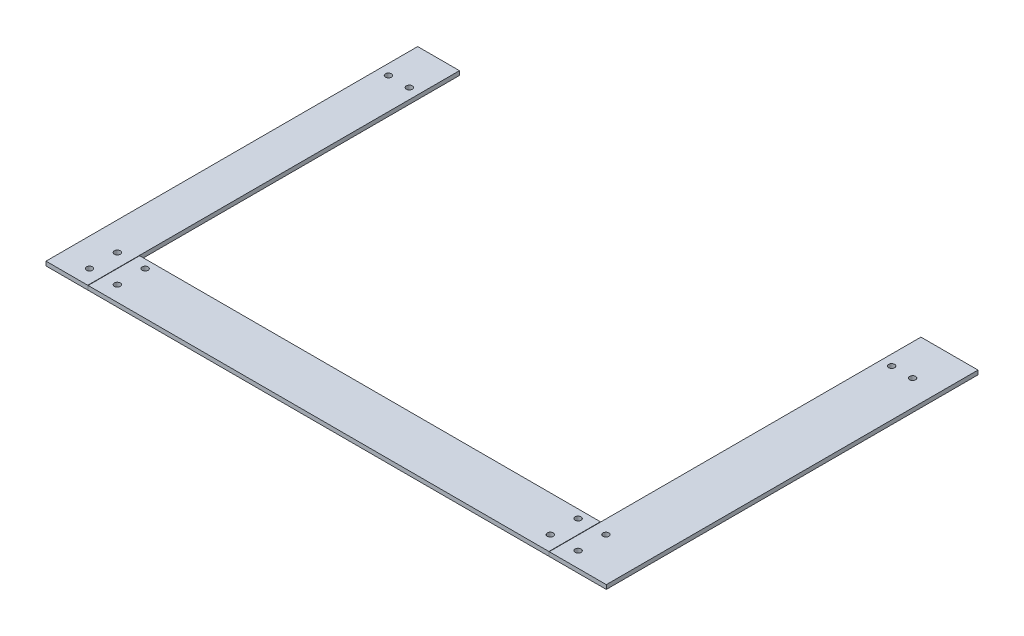
SolidWorks part; units mm, degrees
ref_plane "Front Plane" through (0, 0, 0) normal (0, 0, 1) x (1, 0, 0)
ref_plane "Top Plane" through (0, 0, 0) normal (0, 1, 0) x (1, 0, 0)
ref_plane "Right Plane" through (0, 0, 0) normal (1, 0, 0) x (0, 0, -1)
sketch "Sketch1" plane through (0, 0, 0) normal (0, 1, 0) x (1, 0, 0)
  line L1 (165.75, -135.5) -> (206.75, -135.5)
  line L2 (165.75, -135.5) -> (165.75, 131.5)
  line L3 (165.75, 131.5) -> (206.75, 131.5)
  line L4 (206.75, -135.5) -> (206.75, 131.5)
  line L5 (165.75, -135.5) -> (206.75, 131.5) construction
  line L6 (165.75, 131.5) -> (206.75, -135.5) construction
  point P0 (186.25, -2)
  dimension "D1" = 267
  dimension "D2" = 41
  dimension "D3" = 165.75
  dimension "D4" = 2
extrude "Boss-Extrude1" add sketch "Sketch1" along normal blind 3
sketch "Sketch2" plane through (0, 0, 0) normal (0, 1, 0) x (1, 0, 0)
  line L1 (-195.75, -135.5) -> (-165.75, -135.5)
  line L2 (-195.75, -135.5) -> (-195.75, 131.5)
  line L3 (-195.75, 131.5) -> (-165.75, 131.5)
  line L4 (-165.75, -135.5) -> (-165.75, 131.5)
  line L5 (-195.75, -135.5) -> (-165.75, 131.5) construction
  line L6 (-195.75, 131.5) -> (-165.75, -135.5) construction
  point P0 (-180.75, -2)
  dimension "D1" = 30
  dimension "D2" = 267
  dimension "D3" = 2
  dimension "D4" = 165.75
extrude "Boss-Extrude2" add sketch "Sketch2" along normal blind 3 separate body
sketch "Sketch3" plane through (0, 0, 0) normal (0, 1, 0) x (1, 0, 0)
  line L0 (-195.75, -135.5) -> (-165.75, -135.5) construction
  line L1 (-165.5, -135.5) -> (165.5, -135.5)
  line L2 (-165.5, -135.5) -> (-165.5, -98.5)
  line L3 (-165.5, -98.5) -> (165.5, -98.5)
  line L4 (165.5, -135.5) -> (165.5, -98.5)
  line L5 (-165.5, -135.5) -> (165.5, -98.5) construction
  line L6 (-165.5, -98.5) -> (165.5, -135.5) construction
  point P0 (0, -117)
  dimension "D1" = 331
  dimension "D2" = 37
extrude "Boss-Extrude3" add sketch "Sketch3" along normal blind 3 separate body
hole_wizard "M4 Clearance Hole1" positions "Sketch5" profile "Sketch6" hole size "M4" standard "ANSI Metric" end condition through all
sketch "Sketch5" plane through (0, 3, 0) normal (0, 1, 0) x (1, 0, 0)
  line L1 (-175.5, -124.5) -> (-155.5, -124.5)
  line L2 (-175.5, -124.5) -> (-175.5, -104.5)
  line L3 (-175.5, -104.5) -> (-155.5, -104.5)
  line L4 (-155.5, -124.5) -> (-155.5, -104.5)
  line L5 (-175.5, -124.5) -> (-155.5, -104.5) construction
  line L6 (-175.5, -104.5) -> (-155.5, -124.5) construction
  line L9 (-173.25, 103) -> (-188.25, 103)
  line L11 (-180.75, 131.5) -> (-180.75, 103)
  line L12 (-165.75, 131.5) -> (-195.75, 131.5) construction
  line L13 (165.5, -98.5) -> (-165.5, -98.5) construction
  point P2 (-155.5, -104.5)
  point P45 (-175.5, -124.5)
  point P46 (-175.5, -104.5)
  point P47 (-155.5, -124.5)
  point P65 (-188.25, 103)
  point P67 (-173.25, 103)
  point P84 (-165.5, -114.5)
  dimension "D1" = 20
  dimension "D2" = 20
  dimension "D3" = 15
  dimension "D4" = 28.5
  dimension "D5" = 16
sketch "Sketch6" plane through (-155.5, 3, 104.5) normal (1, 0, 0) x (0, 0, 1)
  line L0 (0, 0) -> (0, 3)
  line L1 (0, 3) -> (2.15, 3)
  line L2 (2.15, 3) -> (2.15, 0)
  line L5 (2.15, 0) -> (0, 0)
  line L11 (0, -6.35) -> (0, 107.95) construction
  dimension "Thru Hole Dia." = 4.3
  dimension "Thru Hole Depth" = 3
mirror "Mirror1" about plane through (0, 0, 0) normal (1, 0, 0) of "M4 Clearance Hole1"
